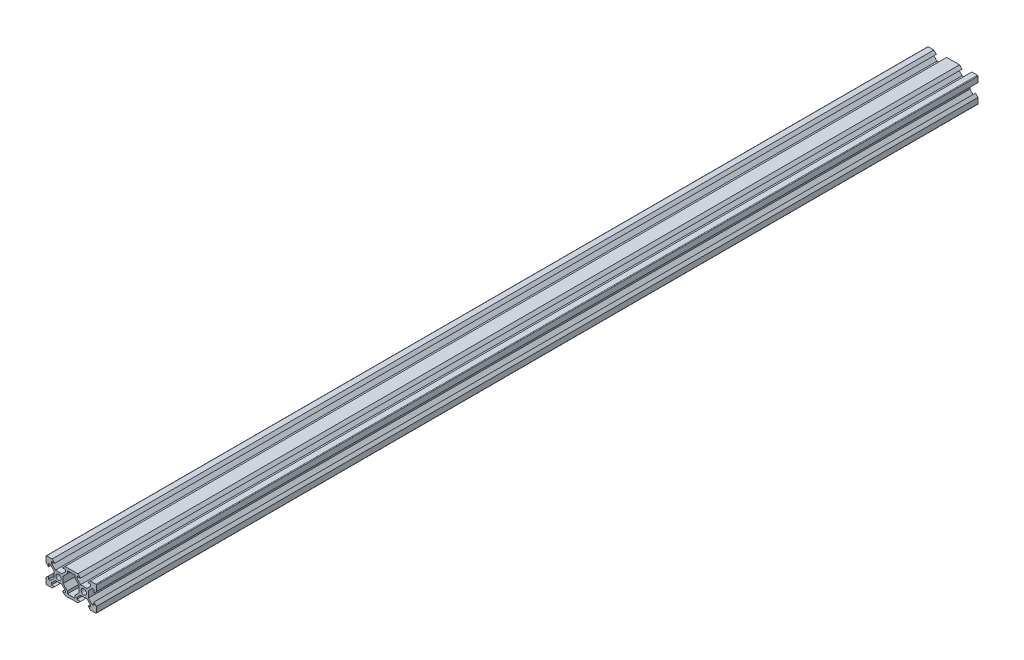
SolidWorks part; units mm, degrees
material "6063-T5"
ref_plane "Front Plane" through (0, 0, 0) normal (0, 0, 1) x (1, 0, 0)
ref_plane "Top Plane" through (0, 0, 0) normal (0, 1, 0) x (1, 0, 0)
ref_plane "Right Plane" through (0, 0, 0) normal (1, 0, 0) x (0, 0, -1)
sketch "Sketch1" plane through (0, 0, 0) normal (0, 0, 1) x (1, 0, 0)
  line L0 (-26.1395, 0) -> (11.0607, 0) construction
  line L1 (0, -20.0817) -> (0, 17.1243) construction
  line L2 (-20, 10.7318) -> (-20, -11.6858) construction
  line L3 (20, 11.8444) -> (20, -11.2237) construction
  line L4 (-23.1467, 10) -> (24.2381, 10) construction
  line L5 (23.8217, -10) -> (-26.7834, -10) construction
  line L6 (3, -5.9393) -> (3, -8)
  line L7 (-20, -10) -> (-15.5, -10)
  line L8 (-20, -10) -> (-20, -5.5)
  line L9 (-18, -5.5) -> (-16.5607, -5.5)
  line L10 (-15.5, -8) -> (-15.5, -6.5607)
  line L11 (-20, 10) -> (-15.5, 10)
  line L12 (-20, 10) -> (-20, 5.5)
  line L13 (-18, 5.5) -> (-16.5607, 5.5)
  line L14 (-15.5, 8) -> (-15.5, 6.5607)
  line L15 (20, 10) -> (15.5, 10)
  line L16 (20, 10) -> (20, 5.5)
  line L17 (18, 5.5) -> (16.5607, 5.5)
  line L18 (15.5, 8) -> (15.5, 6.5607)
  line L19 (20, -10) -> (15.5, -10)
  line L20 (20, -10) -> (20, -5.5)
  line L21 (18, -5.5) -> (16.5607, -5.5)
  line L22 (15.5, -8) -> (15.5, -6.5607)
  line L23 (4.5, -6.5607) -> (4.5, -8)
  line L24 (12.5393, 3.6) -> (15.5, 6.5607)
  line L25 (7.4607, -3.6) -> (4.5, -6.5607)
  line L27 (-4.5, 8) -> (-6.9, 8)
  line L28 (-12.5393, -3.6) -> (-15.5, -6.5607)
  line L29 (7.4607, 3.6) -> (4.5, 6.5607)
  line L30 (12.5393, -3.6) -> (15.5, -6.5607)
  line L31 (-13.6, -2.5393) -> (-16.5607, -5.5)
  line L32 (-13.6, 2.5393) -> (-16.5607, 5.5)
  line L33 (6.4, -2.5393) -> (3, -5.9393)
  line L34 (20, 5.5) -> (20, 5.1)
  line L35 (20, 5.1) -> (18, 3.1)
  line L36 (18, 3.1) -> (18, 5.5)
  line L37 (20, -5.5) -> (20, -5.1)
  line L38 (20, -5.1) -> (18, -3.1)
  line L39 (18, -3.1) -> (18, -5.5)
  line L40 (15.5, 10) -> (15.1, 10)
  line L41 (15.1, 10) -> (13.1, 8)
  line L42 (13.1, 8) -> (15.5, 8)
  line L43 (15.5, -10) -> (15.1, -10)
  line L44 (15.1, -10) -> (13.5138, -8)
  line L45 (13.5138, -8) -> (15.5, -8)
  line L46 (-15.5, 10) -> (-15.1, 10)
  line L47 (-15.1, 10) -> (-13.1, 8)
  line L48 (-13.1, 8) -> (-15.5, 8)
  line L49 (-20, 5.5) -> (-20, 5.1)
  line L50 (-20, 5.1) -> (-18, 3.1)
  line L51 (-18, 3.1) -> (-18, 5.5)
  line L52 (-20, -5.5) -> (-20, -5.1)
  line L53 (-20, -5.1) -> (-18, -3.1)
  line L54 (-18, -3.1) -> (-18, -5.5)
  line L55 (-15.5, -10) -> (-15.1, -10)
  line L56 (-15.1, -10) -> (-13.1, -8)
  line L57 (-13.1, -8) -> (-15.5, -8)
  line L58 (6.4, 2.5393) -> (3, 5.9393)
  line L59 (3, 8) -> (-3, 8)
  line L61 (-3, 5.9393) -> (-3, 8)
  line L62 (-12.5393, 3.6) -> (-15.5, 6.5607)
  line L63 (-4.5, 6.5607) -> (-4.5, 8)
  line L64 (4.5, 6.5607) -> (4.5, 8)
  line L65 (3, 5.9393) -> (3, 8)
  line L66 (13.6, 2.5393) -> (16.5607, 5.5)
  line L67 (12.1, 0) -> (30.0509, 0) construction
  line L68 (-7.4607, 3.6) -> (-4.5, 6.5607)
  line L69 (3, -8) -> (-3, -8)
  line L70 (-6.4, 2.5393) -> (-3, 5.9393)
  line L71 (13.6, -2.5393) -> (16.5607, -5.5)
  line L73 (-3, -5.9393) -> (-3, -8)
  line L74 (-4.5, -6.5607) -> (-4.5, -8)
  line L75 (-7.4607, -3.6) -> (-4.5, -6.5607)
  line L76 (-6.4, -2.5393) -> (-3, -5.9393)
  line L77 (5.3138, -10) -> (7.3138, -8)
  line L78 (7.3138, -8) -> (4.5, -8)
  line L79 (-6.9, -8) -> (-4.9, -10)
  line L80 (-4.9, -10) -> (5.3138, -10)
  line L81 (5.3138, 10) -> (7.3138, 8)
  line L82 (-4.9, 10) -> (5.3138, 10)
  line L83 (-6.9, 8) -> (-4.9, 10)
  line L84 (7.3138, 8) -> (4.5, 8)
  line L85 (7.4607, -3.6) -> (12.5393, -3.6)
  line L86 (-7.4607, -3.6) -> (-12.5393, -3.6)
  line L87 (-6.4, -2.5393) -> (-6.4, 2.5393)
  line L88 (-7.4607, 3.6) -> (-12.5393, 3.6)
  line L89 (-13.6, -2.5393) -> (-13.6, 2.5393)
  line L90 (6.4, -2.5393) -> (6.4, 2.5393)
  line L91 (13.6, -2.5393) -> (13.6, 2.5393)
  line L92 (7.4607, 3.6) -> (12.5393, 3.6)
  line L93 (-4.5, -8) -> (-6.9, -8)
  circle A0 centre (-10, 0) radius 2.1
  circle A1 centre (10, 0) radius 2.1
  dimension "D2" = 4.2
  dimension "D5" = 45
  dimension "D6" = 45
  dimension "D7" = 6.2
  dimension "D8" = 6.2
  dimension "D11" = 3.6
  dimension "D12" = 3.6
  dimension "D38" = 2.4
  dimension "D39" = 45
  dimension "D40" = 2.4
  dimension "D41" = 45
  dimension "D42" = 2
  dimension "D43" = 45
  dimension "D44" = 2.4
  dimension "D45" = 2
  dimension "D49" = 11
extrude "Boss-Extrude1" add sketch "Sketch1" along normal blind 700
fillet "Fillet1" radius 0.5 4 edges at (-20, -10, 350) (-20, 10, 350) (20, -10, 350) (20, 10, 350)
